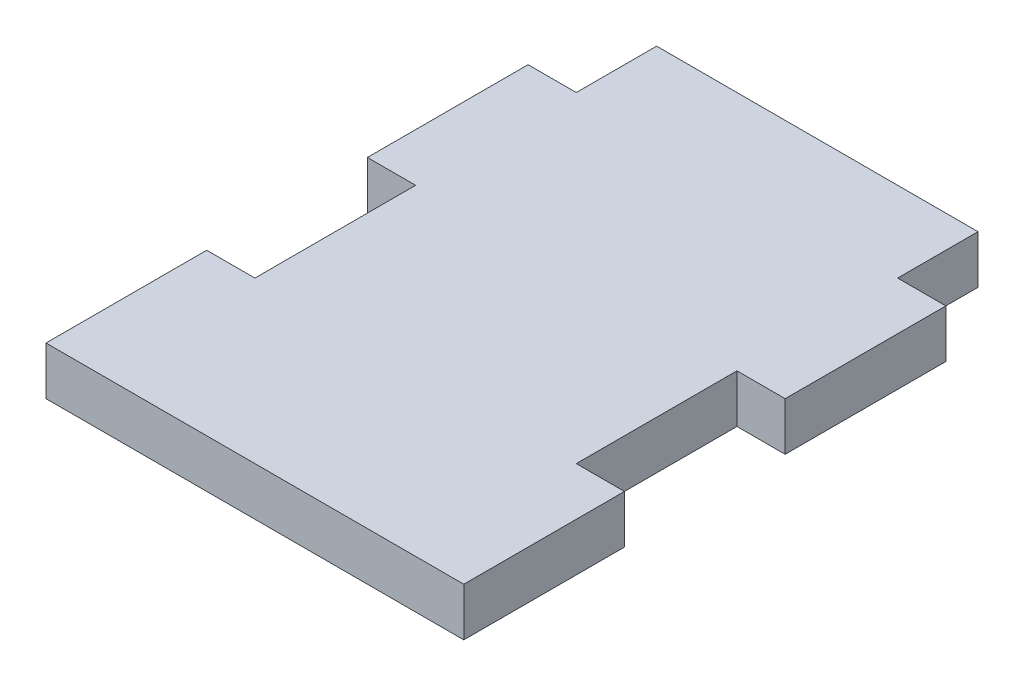
SolidWorks part; units mm, degrees
ref_plane "前视基准面" through (0, 0, 0) normal (0, 0, 1) x (1, 0, 0)
ref_plane "上视基准面" through (0, 0, 0) normal (0, 1, 0) x (1, 0, 0)
ref_plane "右视基准面" through (0, 0, 0) normal (1, 0, 0) x (0, 0, -1)
other "Configuration Table"
sketch "草图1" plane through (0, 0, 0) normal (0, 1, 0) x (1, 0, 0)
  line L0 (0, -9.2726) -> (0, -25.9243) construction
  line L1 (-10, 17.5) -> (10, 17.5)
  line L2 (-10, 17.5) -> (-10, -17.5)
  line L3 (-10, -17.5) -> (10, -17.5)
  line L4 (10, 17.5) -> (10, -17.5)
  line L5 (-10, 17.5) -> (10, -17.5) construction
  line L6 (-10, -17.5) -> (10, 17.5) construction
  line L7 (10, -17.5) -> (13, -17.5)
  line L8 (10, -17.5) -> (10, -7.5)
  line L9 (10, -7.5) -> (13, -7.5)
  line L10 (13, -17.5) -> (13, -7.5)
  line L11 (-10, -7.5) -> (-13, -7.5)
  line L12 (10, 2.5) -> (13, 2.5)
  line L13 (10, 2.5) -> (10, 12.5)
  line L14 (10, 12.5) -> (13, 12.5)
  line L15 (13, 2.5) -> (13, 12.5)
  line L16 (-13, -17.5) -> (-13, -7.5)
  line L17 (-10, -17.5) -> (-13, -17.5)
  line L18 (-10, -17.5) -> (-10, -7.5)
  line L19 (-10, 12.5) -> (-13, 12.5)
  line L20 (-13, 2.5) -> (-13, 12.5)
  line L21 (-10, 2.5) -> (-13, 2.5)
  line L22 (-10, 2.5) -> (-10, 12.5)
  point P0 (0, 0)
  dimension "D1" = 35
  dimension "D2" = 20
  dimension "D3" = 3
  dimension "D4" = 10
  dimension "D5" = 10
extrude "凸台-拉伸1" add sketch "草图1" along normal blind 3 contours L4 L1 L2 L3 | L12 L15 L14 L4 | L7 L10 L9 L4 | L17 L2 L11 L16 | L20 L19 L22 L21
